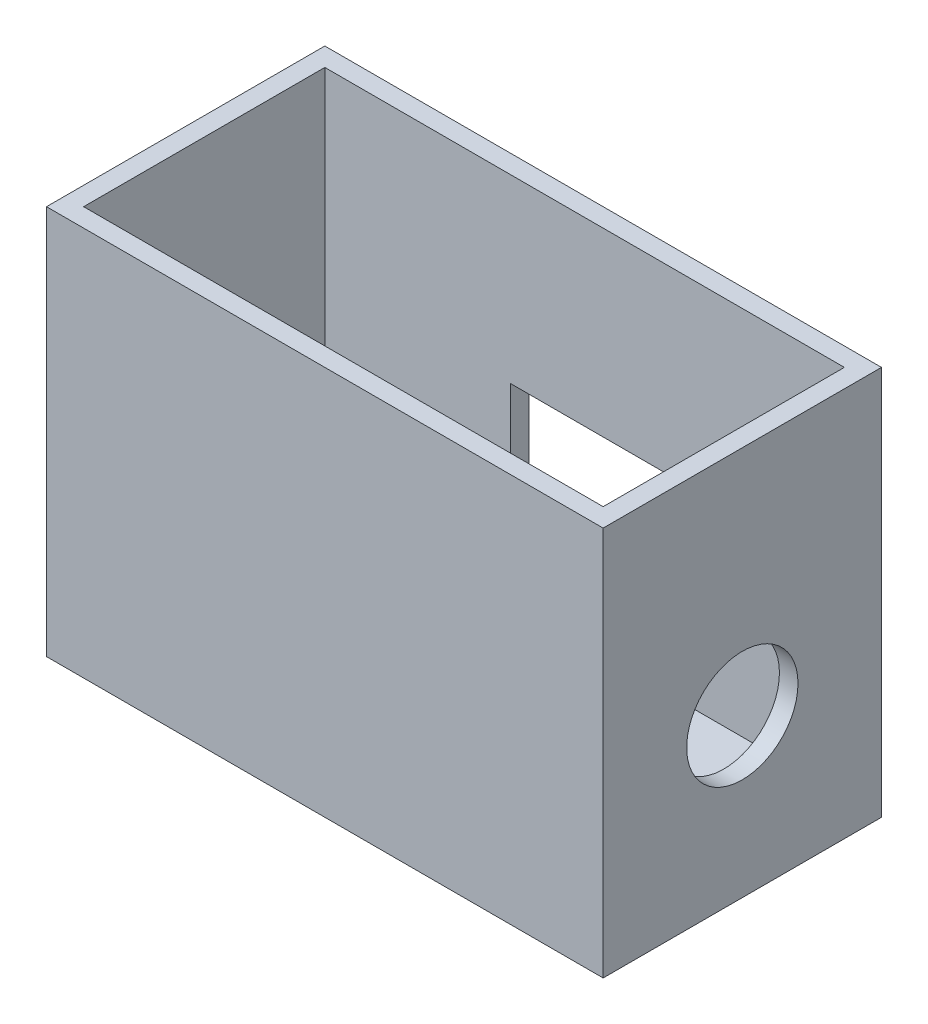
SolidWorks part; units mm, degrees
ref_plane "Front Plane" through (0, 0, 0) normal (0, 0, 1) x (1, 0, 0)
ref_plane "Top Plane" through (0, 0, 0) normal (0, 1, 0) x (1, 0, 0)
ref_plane "Right Plane" through (0, 0, 0) normal (1, 0, 0) x (0, 0, -1)
sketch "Sketch1" plane through (0, 0, 0) normal (0, 1, 0) x (1, 0, 0)
  line L1 (0, 0) -> (60, 0)
  line L2 (0, 0) -> (0, -30)
  line L3 (0, -30) -> (60, -30)
  line L4 (60, 0) -> (60, -30)
  dimension "D1" = 30
  dimension "D2" = 60
extrude "Boss-Extrude1" add sketch "Sketch1" along normal blind 2
sketch "Sketch2" plane through (0, 2, 0) normal (0, 1, 0) x (1, 0, 0)
  line L0 (60, -30) -> (60, 0) construction
  line L1 (0, 0) -> (60, 0)
  line L2 (0, 0) -> (0, -2)
  line L3 (0, -2) -> (60, -2)
  line L4 (60, 0) -> (60, -2)
  dimension "D1" = 2
extrude "Boss-Extrude2" add sketch "Sketch2" along normal blind 40 contours L1 L4 L3 L2
sketch "Sketch3" plane through (0, 2, 0) normal (0, 1, 0) x (1, 0, 0)
  line L0 (60, -30) -> (60, -2) construction
  line L1 (0, -30) -> (60, -30)
  line L2 (0, -30) -> (0, -28)
  line L3 (0, -28) -> (60, -28)
  line L4 (60, -30) -> (60, -28)
  dimension "D1" = 2
extrude "Boss-Extrude3" add sketch "Sketch3" along normal blind 40
sketch "Sketch4" plane through (0, 2, 0) normal (0, 1, 0) x (1, 0, 0)
  line L0 (60, -28) -> (0, -28) construction
  line L1 (0, -2) -> (2, -2)
  line L2 (0, -2) -> (0, -28)
  line L3 (0, -28) -> (2, -28)
  line L4 (2, -2) -> (2, -28)
  dimension "D1" = 2
extrude "Boss-Extrude4" add sketch "Sketch4" along normal blind 40
sketch "Sketch5" plane through (0, 2, 0) normal (0, 1, 0) x (1, 0, 0)
  line L0 (60, -28) -> (2, -28) construction
  line L1 (60, -2) -> (58, -2)
  line L2 (60, -2) -> (60, -28)
  line L3 (60, -28) -> (58, -28)
  line L4 (58, -2) -> (58, -28)
  dimension "D1" = 2
extrude "Boss-Extrude5" add sketch "Sketch5" along normal blind 40
sketch "Sketch7" plane through (60, 0, 0) normal (1, 0, 0) x (0, 0, -1)
  line L0 (-30, 42) -> (-30, 0) construction
  line L2 (0, 42) -> (-30, 42) construction
  circle A0 centre (-15, 17) radius 6
  point P2 (0, 0)
  dimension "D3" = 12
  dimension "D1" = 15
  dimension "D2" = 25
extrude "Cut-Extrude3" cut sketch "Sketch7" against normal up to next contours A0
sketch "Sketch8" plane through (0, 0, 0) normal (0, 0, -1) x (-1, 0, 0)
  line L0 (-60, 42) -> (-60, 0) construction
  line L1 (-40, 22.5) -> (-22, 22.5)
  line L2 (-40, 22.5) -> (-40, 10)
  line L3 (-40, 10) -> (-22, 10)
  line L4 (-22, 22.5) -> (-22, 10)
  line L5 (-60, 0) -> (0, 0) construction
  dimension "D1" = 12.5
  dimension "D2" = 18
  dimension "D3" = 20
  dimension "D4" = 10
extrude "Cut-Extrude4" cut sketch "Sketch8" against normal up to next
